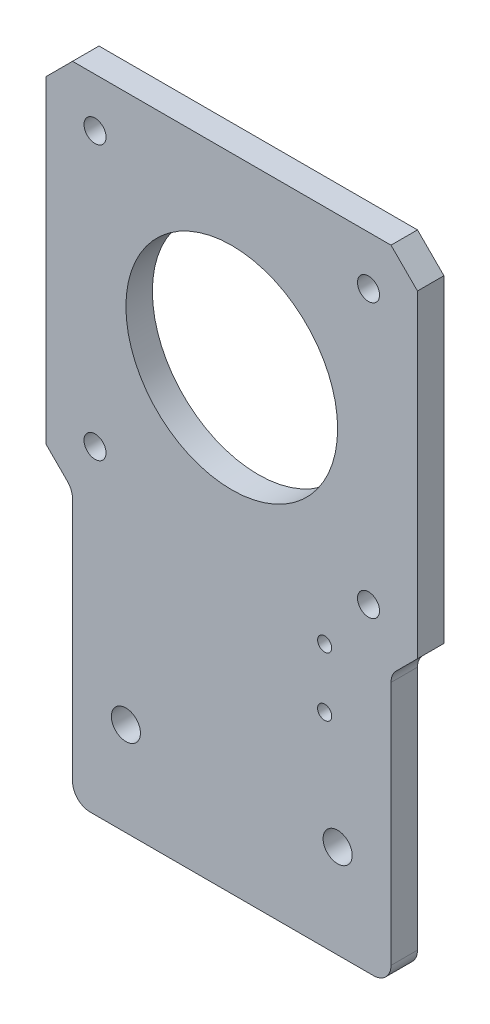
SolidWorks part; units mm, degrees
ref_plane "Plano frontal" through (0, 0, 0) normal (0, 0, 1) x (1, 0, 0)
ref_plane "Plano superior" through (0, 0, 0) normal (0, 1, 0) x (1, 0, 0)
ref_plane "Plano direito" through (0, 0, 0) normal (1, 0, 0) x (0, 0, -1)
sketch "Sketch1" plane through (0, 0, 0) normal (0, 0, 1) x (1, 0, 0)
  line L1 (-18.05, -21.05) -> (18.05, -21.05) construction
  line L2 (18.05, -51.655) -> (18.05, -21.05)
  line L4 (-18.05, -51.655) -> (-18.05, -21.05)
  line L5 (18.05, -51.655) -> (-18.05, -51.655)
  line L16 (-21.05, -18.05) -> (-18.05, -21.05)
  line L18 (18.05, -21.05) -> (21.05, -18.05)
  line L19 (21.05, -18.05) -> (21.05, 18.05)
  line L20 (21.05, 18.05) -> (18.05, 21.05)
  line L21 (18.05, 21.05) -> (-18.05, 21.05)
  line L22 (-18.05, 21.05) -> (-21.05, 18.05)
  line L23 (-21.05, 18.05) -> (-21.05, -18.05)
  circle A3 centre (0, 0) radius 12
  dimension "D2" = 36.1
  dimension "D3" = 4.2426
  dimension "D1" = 30.605
extrude "Boss-Extrude1" add sketch "Sketch1" along normal blind 3
hole_wizard "Tap Drill for M3 Tap1" positions "Sketch3" profile "Sketch2" hole size "M3" standard "ISO"
sketch "Sketch3" plane through (0, 0, 3) normal (0, 0, 1) x (1, 0, 0)
  point P0 (-15.5, 15.5)
  point P3 (15.5, 15.5)
  point P6 (-15.5, -15.5)
  point P9 (15.5, -15.5)
sketch "Sketch2" plane through (-15.5, 15.5, 3) normal (1, 0, 0) x (0, -1, 0)
  line L0 (0, 0) -> (0, 5.7511)
  line L1 (0, 5.7511) -> (1.25, 5)
  line L2 (1.25, 5) -> (1.25, 0)
  line L5 (1.25, 0) -> (0, 0)
  line L10 (0, 5.7511) -> (-1.25, 5) construction
  line L11 (0, -6.35) -> (0, 107.95) construction
  dimension "Hole Dia." = 2.5
  dimension "Hole Depth" = 5
  dimension "Drill Angle" = 118
hole_wizard "Tap Drill for M4 Tap1" positions "Sketch5" profile "Sketch4" hole size "M4" standard "ISO"
sketch "Sketch5" plane through (0, 0, 3) normal (0, 0, 1) x (1, 0, 0)
  line L1 (0, -51.655) -> (0, -21.05) construction
  line L2 (-18.05, -51.655) -> (18.05, -51.655) construction
  line L3 (149.1978, -41.055) -> (-642.8022, -41.055) construction
  point P11 (12, -41.055)
  point P27 (-12, -41.055)
  dimension "D1" = 12
sketch "Sketch4" plane through (-12, -41.055, 3) normal (1, 0, 0) x (0, -1, 0)
  line L0 (0, 0) -> (0, 5.9914)
  line L1 (0, 5.9914) -> (1.65, 5)
  line L2 (1.65, 5) -> (1.65, 0)
  line L5 (1.65, 0) -> (0, 0)
  line L10 (0, 5.9914) -> (-1.65, 5) construction
  line L11 (0, -6.35) -> (0, 107.95) construction
  dimension "Hole Dia." = 3.3
  dimension "Hole Depth" = 5
  dimension "Drill Angle" = 118
fillet "Fillet1" radius 2 4 edges at (18.05, -21.05, 1.5) (18.05, -51.655, 1.5) (-18.05, -51.655, 1.5) (-18.05, -21.05, 1.5)
hole_wizard "Tap Drill for M2 Tap1" positions "Sketch7" profile "Sketch6" hole size "M2" standard "ISO"
sketch "Sketch7" plane through (0, 0, 3) normal (0, 0, 1) x (1, 0, 0)
  point P0 (10.5295, -21.8613)
  point P3 (10.5295, -28.5613)
sketch "Sketch6" plane through (10.5295, -21.8613, 3) normal (1, 0, 0) x (0, -1, 0)
  line L0 (0, 0) -> (0, 5.4807)
  line L1 (0, 5.4807) -> (0.8, 5)
  line L2 (0.8, 5) -> (0.8, 0)
  line L5 (0.8, 0) -> (0, 0)
  line L10 (0, 5.4807) -> (-0.8, 5) construction
  line L11 (0, -6.35) -> (0, 107.95) construction
  dimension "Hole Dia." = 1.6
  dimension "Hole Depth" = 5
  dimension "Drill Angle" = 118
